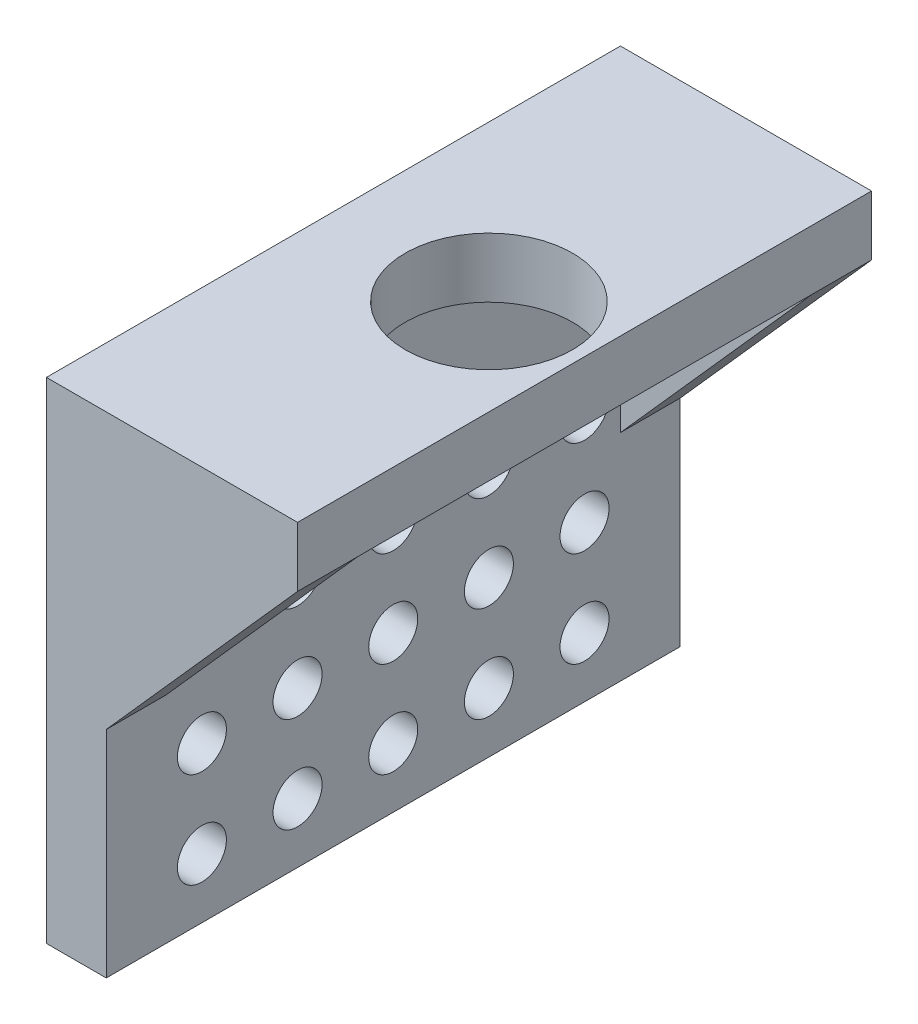
SolidWorks part; units mm, degrees
material "PMMA"
ref_plane "Front Plane" through (0, 0, 0) normal (0, 0, 1) x (1, 0, 0)
ref_plane "Top Plane" through (0, 0, 0) normal (0, 1, 0) x (1, 0, 0)
ref_plane "Right Plane" through (0, 0, 0) normal (1, 0, 0) x (0, 0, -1)
sketch "Sketch1" plane through (0, 0, 0) normal (0, 1, 0) x (1, 0, 0)
  line L0 (0, 0) -> (21, 0)
  line L1 (21, 0) -> (21, -48)
  line L2 (21, -48) -> (0, -48)
  line L3 (0, -48) -> (0, 0)
  line L4 (5, 8.2865) -> (5, -55.9573) construction
  circle A0 centre (13, -24) radius 7
  dimension "D6" = 14
  dimension "D1" = 21
  dimension "D2" = 48
  dimension "D3" = 16
  dimension "D4" = 8
  dimension "D5" = 24
extrude "Boss-Extrude1" add sketch "Sketch1" along normal blind 5
sketch "Sketch2" plane through (0, 0, 0) normal (0, -1, 0) x (1, 0, 0)
  line L0 (0, 48) -> (5, 48)
  line L1 (5, 48) -> (5, 0)
  line L2 (21, 0) -> (0, 0) construction
  line L3 (5, 0) -> (0, 0)
  line L4 (0, 0) -> (0, 48)
  dimension "D1" = 5
extrude "Boss-Extrude2" add sketch "Sketch2" along normal blind 36
sketch "Sketch4" plane through (0, 0, 0) normal (0, -1, 0) x (1, 0, 0)
  line L0 (5, 48) -> (21, 48)
  line L1 (21, 48) -> (21, 43)
  line L2 (21, 48) -> (21, 0) construction
  line L3 (21, 43) -> (5, 43)
  line L4 (5, 0) -> (5, 48) construction
  line L5 (5, 43) -> (5, 48)
  line L6 (0, 24) -> (28.1978, 24) construction
  line L7 (0, 48) -> (0, 0) construction
  line L8 (21, 5) -> (5, 5)
  line L9 (21, 0) -> (21, 5)
  line L10 (5, 0) -> (21, 0)
  line L11 (5, 5) -> (5, 0)
  dimension "D1" = 5
extrude "Boss-Extrude3" add sketch "Sketch4" along normal blind 18
sketch "Sketch5" plane through (0, 0, 48) normal (0, 0, 1) x (1, 0, 0)
  line L0 (21, 0) -> (5, -18)
  line L1 (5, -18) -> (21, -18)
  line L2 (21, -18) -> (21, 0)
extrude "Cut-Extrude1" cut sketch "Sketch5" against normal through all
sketch "Sketch6" plane through (0, 0, 0) normal (-1, 0, 0) x (0, 0, 1)
  line L0 (24, 5) -> (24, -39.1174) construction
  line L1 (0, 5) -> (48, 5) construction
  line L2 (48, -36) -> (0, -36) construction
  circle A0 centre (8, -31) radius 2.05
  circle A1 centre (16, -31) radius 2.05
  circle A2 centre (24, -31) radius 2.05
  circle A3 centre (32, -31) radius 2.05
  circle A4 centre (40, -31) radius 2.05
  circle A5 centre (16, -23) radius 2.05
  circle A6 centre (24, -23) radius 2.05
  circle A7 centre (32, -23) radius 2.05
  circle A8 centre (40, -23) radius 2.05
  circle A9 centre (16, -15) radius 2.05
  circle A10 centre (24, -15) radius 2.05
  circle A11 centre (32, -15) radius 2.05
  circle A12 centre (40, -15) radius 2.05
  circle A13 centre (8, -23) radius 2.05
  circle A14 centre (8, -15) radius 2.05
  dimension "D1" = 4.1
  dimension "D2" = 16
  dimension "D3" = 5
  dimension "D6" = 16
  dimension "D7" = 32
  dimension "D4" = 5
  dimension "D5" = 3
extrude "Cut-Extrude2" cut sketch "Sketch6" against normal blind 18
